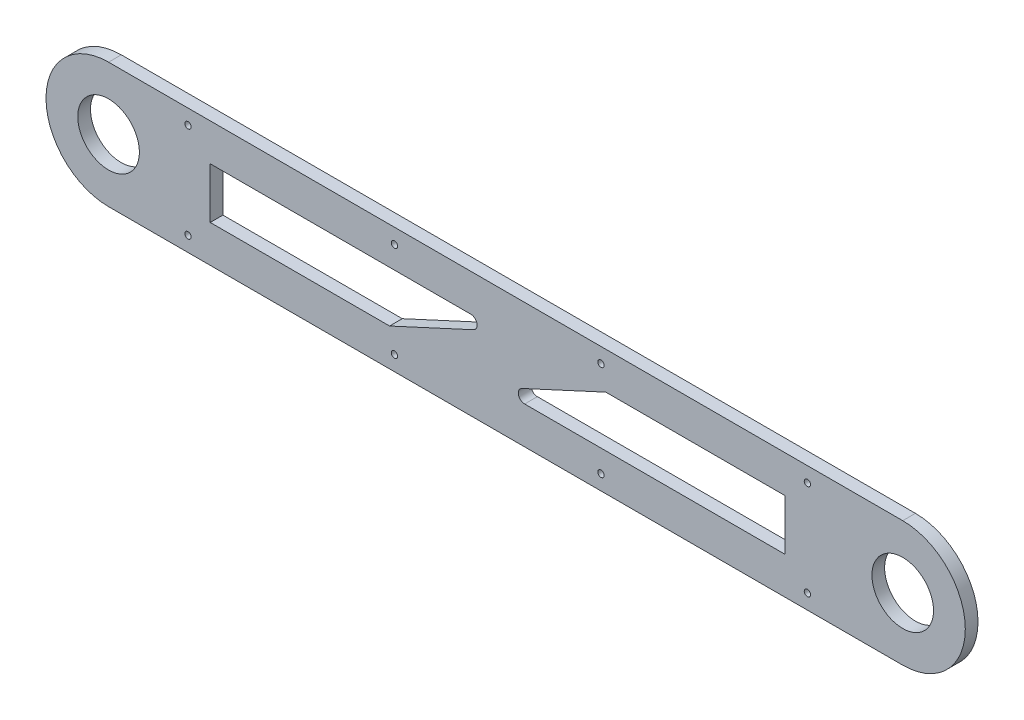
SolidWorks part; units mm, degrees
ref_plane "前视基准面" through (0, 0, 0) normal (0, 0, 1) x (1, 0, 0)
ref_plane "上视基准面" through (0, 0, 0) normal (0, 1, 0) x (1, 0, 0)
ref_plane "右视基准面" through (0, 0, 0) normal (1, 0, 0) x (0, 0, -1)
sketch "草图1" plane through (0, 0, 0) normal (0, 0, 1) x (1, 0, 0)
  line L0 (0, 0) -> (250, 0) construction
  line L1 (0, 0) -> (0, 15.4343) construction
  line L6 (0, 0) -> (0, -15.4343) construction
  line L7 (0, 19.7) -> (250, 19.7)
  line L8 (0, -19.7) -> (250, -19.7)
  line L9 (250, 0) -> (225.3628, 42.6729) construction
  line L10 (240.15, 17.0607) -> (232.3558, 12.5607) construction
  line L11 (0, 19.7) -> (232.3558, 12.5607) construction
  line L12 (240.15, -17.0607) -> (232.3558, -12.5607) construction
  line L13 (0, -19.7) -> (232.3558, -12.5607) construction
  circle A0 centre (0, 0) radius 9.7
  circle A1 centre (250, 0) radius 9.7
  circle A2 centre (0, 0) radius 19.7 construction
  circle A3 centre (250, 0) radius 19.7 construction
  arc A4 (0, 19.7) -> (0, -19.7) centre (0, 0) ccw
  arc A7 (240.15, -17.0607) -> (250, 19.7) centre (250, 0) ccw construction
  arc A8 (250, 19.7) -> (250, -19.7) centre (250, 0) cw
  dimension "D1" = 10
  dimension "D2" = 19.4
  dimension "D3" = 60
extrude "凸台-拉伸1" add sketch "草图1" along normal blind 4
sketch "草图2" plane through (0, 0, 4) normal (0, 0, 1) x (1, 0, 0)
  line L0 (0, 0) -> (250, 0) construction
  line L1 (0, 0) -> (0, -8.921) construction
  circle A0 centre (25, 15) radius 1
  circle A1 centre (90, 15) radius 1
  circle A2 centre (155, 15) radius 1
  circle A3 centre (220, 15) radius 1
  circle A4 centre (90, -15) radius 1
  circle A5 centre (155, -15) radius 1
  circle A6 centre (220, -15) radius 1
  circle A7 centre (25, -15) radius 1
  dimension "D1" = 2
  dimension "D2" = 25
  dimension "D3" = 15
extrude "切除-拉伸1" cut sketch "草图2" against normal blind 10
sketch "草图3" plane through (0, 0, 4) normal (0, 0, 1) x (1, 0, 0)
  line L4 (32, 8) -> (114.0233, 8)
  line L5 (114.8614, 4.1841) -> (88.4625, -8)
  line L6 (88.4625, -8) -> (32, -8)
  line L7 (32, -8) -> (32, 8)
  line L13 (156.5375, 8) -> (130.1386, -4.1841)
  line L14 (213, -8) -> (130.9767, -8)
  line L15 (213, 8) -> (213, -8)
  line L16 (156.5375, 8) -> (213, 8)
  arc A0 (130.9767, -8) -> (130.1386, -4.1841) centre (130.9767, -6) cw
  arc A1 (114.8614, 4.1841) -> (114.0233, 8) centre (114.0233, 6) ccw
  dimension "D1" = 2
extrude "切除-拉伸2" cut sketch "草图3" against normal blind 10
